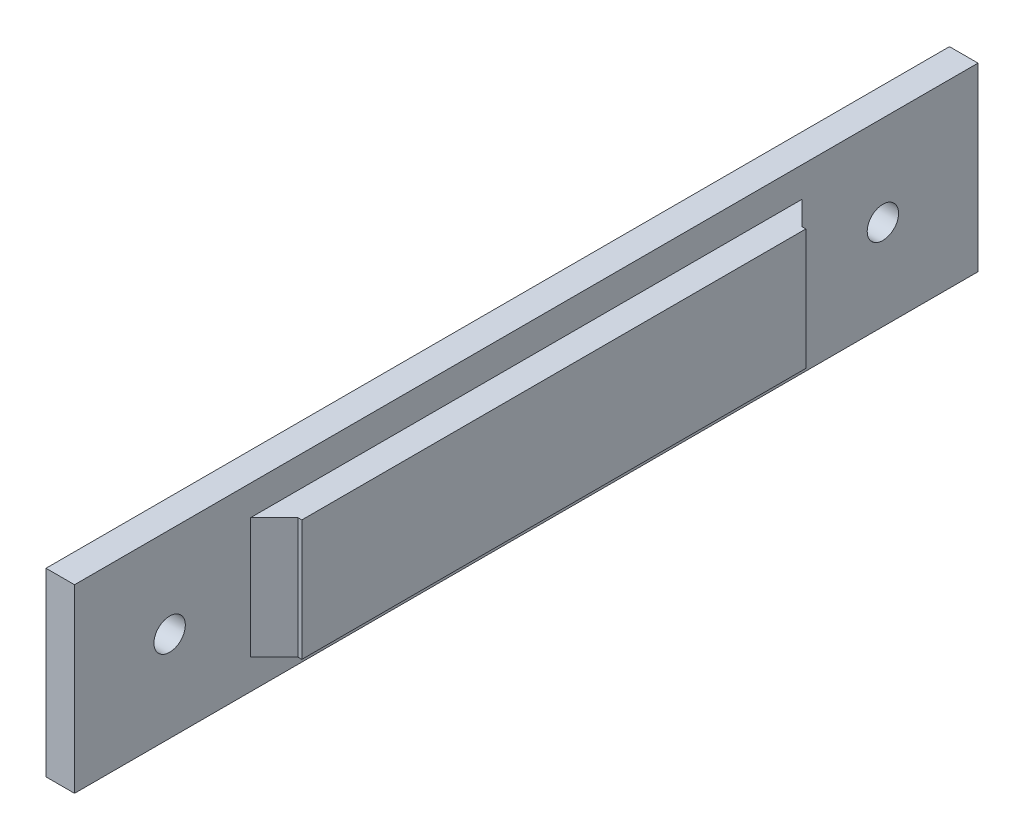
SolidWorks part; units mm, degrees
ref_plane "前视基准面" through (0, 0, 0) normal (0, 0, 1) x (1, 0, 0)
ref_plane "上视基准面" through (0, 0, 0) normal (0, 1, 0) x (1, 0, 0)
ref_plane "右视基准面" through (0, 0, 0) normal (1, 0, 0) x (0, 0, -1)
sketch "草图1" plane through (0, 0, 0) normal (0, 0, 1) x (1, 0, 0)
  line L1 (0, 0) -> (13, 0)
  line L2 (0, 0) -> (0, 13)
  line L3 (0, 13) -> (13, 13)
  line L4 (13, 0) -> (13, 13)
  dimension "D1" = 13
  dimension "D2" = 13
extrude "拉伸-薄壁1" add sketch "草图1" along normal blind 95 thin
sketch "草图2" plane through (-3, 0, 0) normal (-1, 0, 0) x (0, 0, 1)
  line L0 (0, 16) -> (0, -3) construction
  line L1 (95, 16) -> (95, -3) construction
  circle A0 centre (10, 6.5) radius 1.65
  circle A1 centre (85, 6.5) radius 1.65
  dimension "D1" = 3.3
  dimension "D2" = 3.3
  dimension "D3" = 10
  dimension "D4" = 10
extrude "切除-拉伸1" cut sketch "草图2" against normal blind 30
sketch "草图3" plane through (16, 0, 0) normal (1, 0, 0) x (0, 0, -1)
  line L1 (-95, 16) -> (0, 16)
  line L2 (-95, 16) -> (-95, -3)
  line L3 (-95, -3) -> (0, -3)
  line L4 (0, 16) -> (0, -3)
extrude "切除-拉伸2" cut sketch "草图3" against normal blind 16
sketch "草图4" plane through (0, 0, 0) normal (1, 0, 0) x (0, 0, -1)
  line L0 (0, 16) -> (0, -3) construction
  line L1 (-74, 12.85) -> (-21, 12.85)
  line L2 (-74, 12.85) -> (-74, 0.15)
  line L3 (-74, 0.15) -> (-21, 0.15)
  line L4 (-21, 12.85) -> (-21, 0.15)
  line L5 (-95, 16) -> (-95, -3) construction
  line L6 (-95, -3) -> (0, -3) construction
  line L7 (0, 16) -> (-95, 16) construction
  point P8 (-21, 6.5)
  dimension "D1" = 21
  dimension "D2" = 21
  dimension "D3" = 12.7
  dimension "D4" = 9.5
  dimension "D5" = 3.15
  dimension "D6" = 3.15
extrude "凸台-拉伸1" add sketch "草图4" along normal blind 2.9
chamfer "倒角1" distance 2.5 angle 45 2 edges at (0, 6.5, 21) (0, 6.5, 74)
